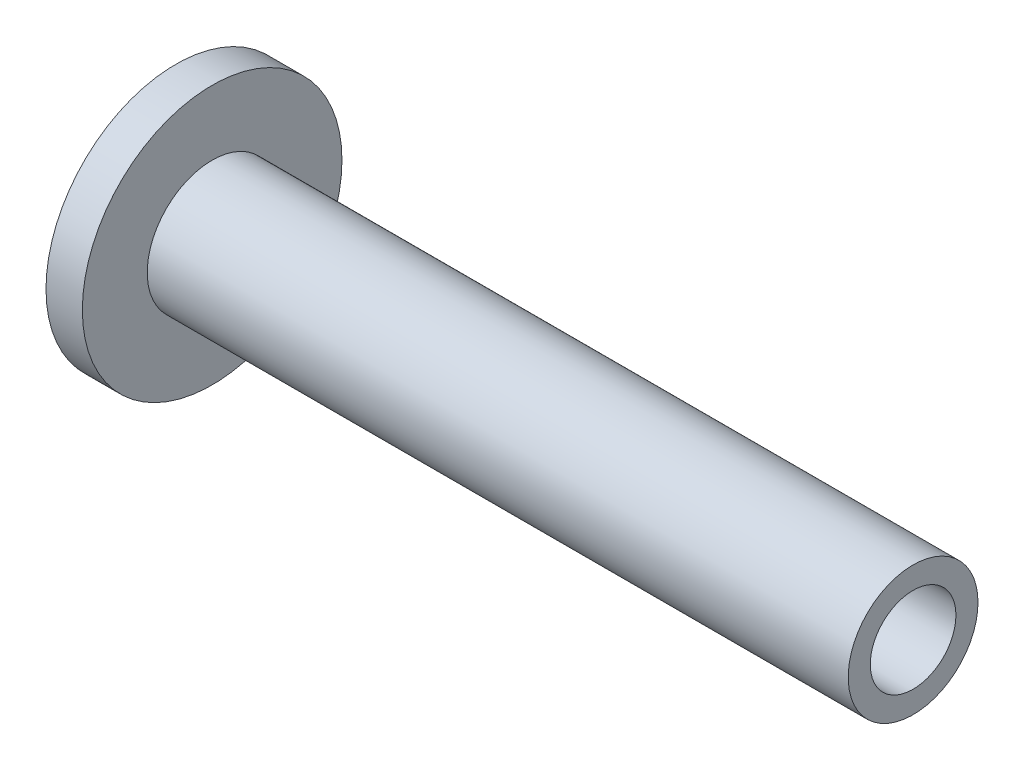
SolidWorks part; units mm, degrees
material "AISI 304"
ref_plane "前视基准面" through (0, 0, 0) normal (0, 0, 1) x (1, 0, 0)
ref_plane "上视基准面" through (0, 0, 0) normal (0, 1, 0) x (1, 0, 0)
ref_plane "右视基准面" through (0, 0, 0) normal (1, 0, 0) x (0, 0, -1)
sketch "草图1" plane through (0, 0, 0) normal (1, 0, 0) x (0, 0, -1)
  circle A0 centre (0, 0) radius 5
  dimension "D1" = 10
extrude "凸台-拉伸1" add sketch "草图1" along normal blind 1.9
sketch "草图2" plane through (1.9, 0, 0) normal (1, 0, 0) x (0, 0, -1)
  circle A0 centre (0, 0) radius 2.5
  dimension "D1" = 5
extrude "凸台-拉伸2" add sketch "草图2" along normal blind 27
hole_wizard "M4 螺纹孔1" positions "3D草图1" profile "草图4" tap size "M4" standard "GB"
sketch3d "3D草图1"
  line L0 (28.9, 0, 0) -> (1.9, 0, 0) construction
  point P3 (28.9, 0, 0)
sketch "草图4" plane through (28.9, 0, 0) normal (0, 1, 0) x (0, 0, -1)
  line L0 (0, 0) -> (0, 11.0914)
  line L1 (0, 11.0914) -> (1.65, 10.1)
  line L2 (1.65, 10.1) -> (1.65, 0)
  line L5 (1.65, 0) -> (0, 0)
  line L10 (0, 11.0914) -> (-1.65, 10.1) construction
  line L11 (0, -6.35) -> (0, 107.95) construction
  dimension "螺纹孔钻头直径" = 3.3
  dimension "螺纹孔钻头深度" = 10.1
  dimension "导头角度" = 118
cosmetic thread "孔螺蚊线1"
chamfer "倒角1" distance 0.5 angle 60 1 edges at (0, 0, -5)
